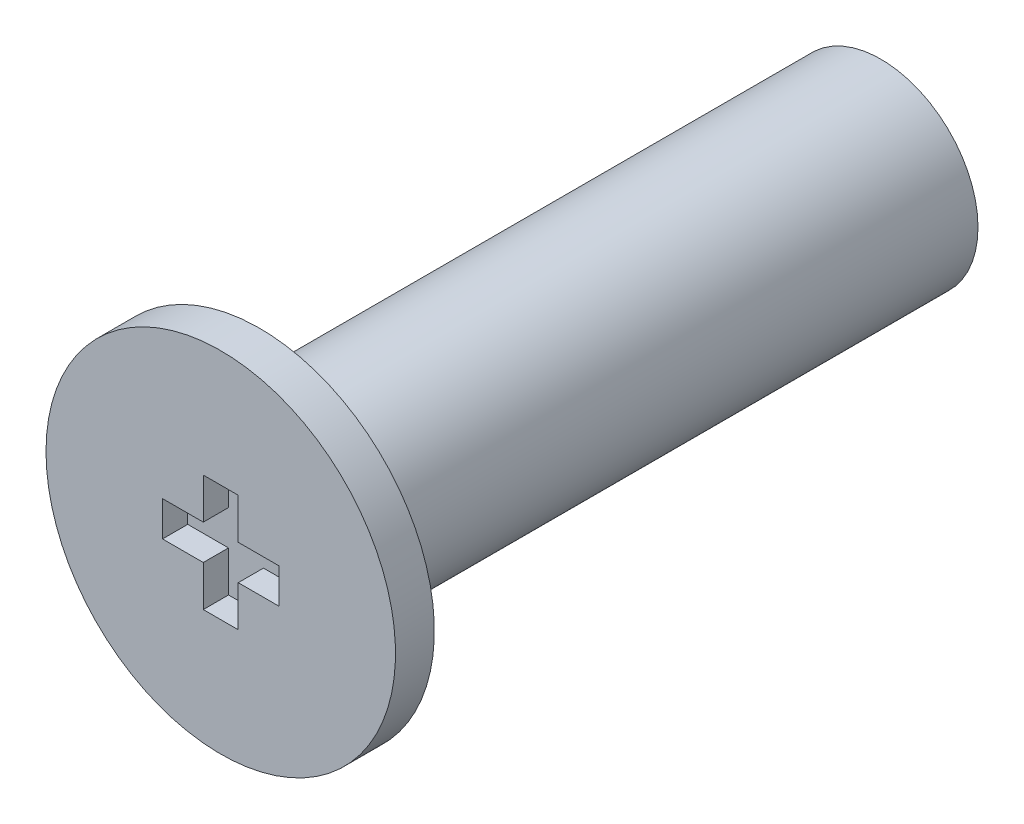
SolidWorks part; units mm, degrees
ref_plane "前视基准面" through (0, 0, 0) normal (0, 0, 1) x (1, 0, 0)
ref_plane "上视基准面" through (0, 0, 0) normal (0, 1, 0) x (1, 0, 0)
ref_plane "右视基准面" through (0, 0, 0) normal (1, 0, 0) x (0, 0, -1)
other "Configuration Table"
sketch "草图1" plane through (0, 0, 0) normal (0, 0, 1) x (1, 0, 0)
  circle A0 centre (0, 0) radius 2.5
extrude "标准杆径_头下长度" add sketch "草图1" against normal blind 16
sketch "草图2" plane through (0, 0, 0) normal (0, 0, 1) x (1, 0, 0)
  circle A0 centre (0, 0) radius 4.25
sketch "草图4" plane through (0, 0, 0) normal (0, 1, 0) x (1, 0, 0)
  line L0 (0, 0) -> (5.9, 0)
  line L1 (5.9, 0) -> (5.9, -0.3477)
  line L2 (0, -3.1) -> (0, 0)
  line L3 (0, 2) -> (0, -5.1) construction
  arc A0 (5.9, -0.3477) -> (0, -3.1) centre (0, 4.6) cw
sketch "草图5" plane through (0, 0, 0) normal (0, 0, 1) x (1, 0, 0)
  line L0 (-0.5, -2.5) -> (0.5, -2.5)
  line L1 (0.5, -2.5) -> (0.5, -0.5)
  line L2 (0.5, -0.5) -> (2.5, -0.5)
  line L3 (2.5, -0.5) -> (2.5, 0.5)
  line L4 (2.5, 0.5) -> (0.5, 0.5)
  line L5 (0.5, 0.5) -> (0.5, 2.5)
  line L6 (0.5, 2.5) -> (-0.5, 2.5)
  line L7 (-0.5, 2.5) -> (-0.5, 0.5)
  line L8 (-0.5, 0.5) -> (-2.5, 0.5)
  line L9 (-2.5, 0.5) -> (-2.5, -0.5)
  line L10 (-2.5, -0.5) -> (-0.5, -0.5)
  line L11 (-0.5, -0.5) -> (-0.5, -2.5)
sketch "草图6" plane through (0, 0, 0) normal (0, 1, 0) x (1, 0, 0)
  line L0 (0, 0) -> (4.5, 0)
  line L1 (4.5, 0) -> (4.5, -1)
  line L2 (4.5, -1) -> (0, -1)
  line L3 (0, -1) -> (0, 0)
  line L4 (0, 2) -> (0, -3) construction
revolve "已确认_十字槽超薄头" add sketch "草图6" angle 360 about L4
sketch "草图7" plane through (0, 0, 0) normal (0, 0, 1) x (1, 0, 0)
  line L0 (-0.45, -1.5) -> (0.45, -1.5)
  line L1 (0.45, -1.5) -> (0.45, -0.45)
  line L2 (0.45, -0.45) -> (1.5, -0.45)
  line L3 (1.5, -0.45) -> (1.5, 0.45)
  line L4 (1.5, 0.45) -> (0.45, 0.45)
  line L5 (0.45, 0.45) -> (0.45, 1.5)
  line L6 (0.45, 1.5) -> (-0.45, 1.5)
  line L7 (-0.45, 1.5) -> (-0.45, 0.45)
  line L8 (-0.45, 0.45) -> (-1.5, 0.45)
  line L9 (-1.5, 0.45) -> (-1.5, -0.45)
  line L10 (-1.5, -0.45) -> (-0.45, -0.45)
  line L11 (-0.45, -0.45) -> (-0.45, -1.5)
extrude "十字槽_PH2_简化" cut sketch "草图7" against normal blind 0.66 from offset 1.01
